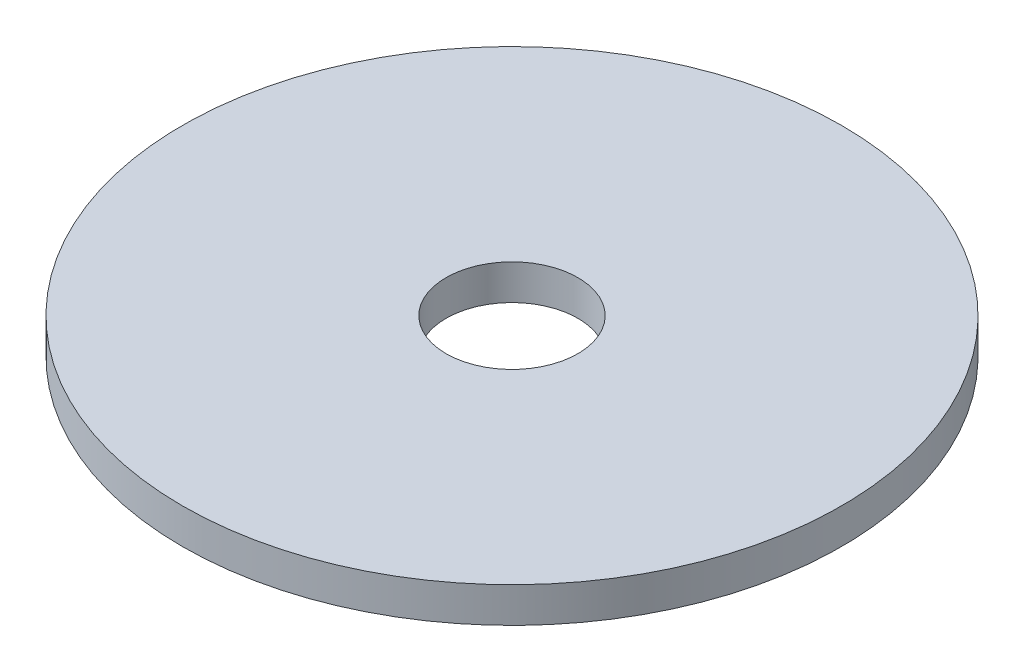
SolidWorks part; units mm, degrees
ref_plane "Front Plane" through (0, 0, 0) normal (0, 0, 1) x (1, 0, 0)
ref_plane "Top Plane" through (0, 0, 0) normal (0, 1, 0) x (1, 0, 0)
ref_plane "Right Plane" through (0, 0, 0) normal (1, 0, 0) x (0, 0, -1)
sketch "Sketch1" plane through (0, 0, 0) normal (1, 0, 0) x (0, 0, -1)
  line L0 (0, 21.8606) -> (0, -19.795) construction
  line L1 (-18.9774, 0) -> (17.2561, 0) construction
  line L3 (-30, 1.6055) -> (-6, 1.6055)
  line L4 (-30, 1.6055) -> (-30, -1.6055)
  line L5 (-30, -1.6055) -> (-6, -1.6055)
  line L6 (-6, 1.6055) -> (-6, -1.6055)
  line L7 (-30, 1.6055) -> (-6, -1.6055) construction
  line L8 (-30, -1.6055) -> (-6, 1.6055) construction
  point P5 (-18, 0)
  point P10 (0, 0)
  dimension "D1" = 12
  dimension "D2" = 60
revolve "Revolve1" add sketch "Sketch1" angle 360 about L0
